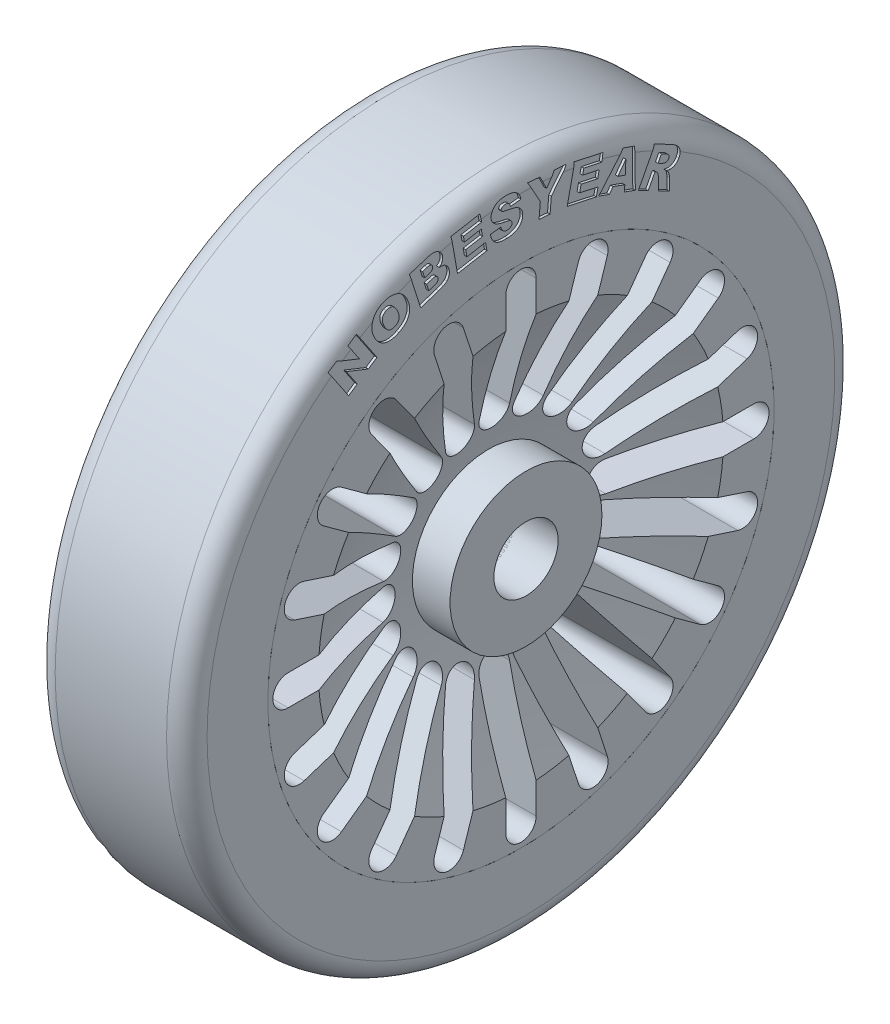
SolidWorks part; units mm, degrees
ref_plane "Front Plane" through (0, 0, 0) normal (0, 0, 1) x (1, 0, 0)
ref_plane "Top Plane" through (0, 0, 0) normal (0, 1, 0) x (1, 0, 0)
ref_plane "Right Plane" through (0, 0, 0) normal (1, 0, 0) x (0, 0, -1)
ref_axis "Axis1" through (-1.5, 0, 0) along (1, 0, 0)
sketch "Sketch1" plane through (0, 0, 0) normal (0, 0, 1) x (1, 0, 0)
  line L0 (-3.75, 0) -> (3.75, 0)
  line L1 (7.5, 20) -> (7.5, 25)
  line L2 (7.5, 25) -> (-7.5, 25)
  line L3 (-7.5, 25) -> (-7.5, 20)
  line L4 (0, -55) -> (0, 55) construction
  line L5 (-1.5, 0) -> (31.5, 0) construction
  arc A0 (3.75, 0) -> (7.5, 20) centre (58.9583, 0) cw
  arc A1 (-7.5, 20) -> (-3.75, 0) centre (-58.9583, 0) cw
  point P2 (0, 0)
  point P10 (0, 25)
  dimension "D1" = 7.5
  dimension "D2" = 15
  dimension "D3" = 25
  dimension "D4" = 5
  dimension "D5" = 5
revolve "Hub" add sketch "Sketch1" angle 360 about L0
sketch "Sketch2" plane through (0, 0, 0) normal (0, 0, 1) x (1, 0, 0)
  line L0 (-7.5, 25) -> (7.5, 25)
  line L1 (7.5, 25) -> (7.5, 33)
  line L2 (-7.5, 33) -> (7.5, 33)
  line L3 (0, -27.5) -> (0, 27.5) construction
  line L5 (-1.5, 0) -> (31.5, 0) construction
  line L15 (-7.5, 33) -> (-7.5, 25)
  point P4 (0, 25)
  dimension "D1" = 8
  dimension "D2" = 25
  dimension "D3" = 15
revolve "Tire" add sketch "Sketch2" angle 360 about axis through (-1.5, 0, 0) along (1, 0, 0)
fillet "Fillet1" radius 2 2 edges at (-7.5, 0, 33) (7.5, 0, 33)
sketch "Sketch3" plane through (0, 0, 0) normal (1, 0, 0) x (0, 0, -1)
  circle A0 centre (0, 0) radius 7.5
  dimension "D1" = 15
extrude "Boss-Extrude1" add sketch "Sketch3" along normal mid plane 16 separate body
sketch "Sketch4" plane through (8, 0, 0) normal (1, 0, 0) x (0, 0, -1)
  circle A0 centre (0, 0) radius 3.175
  dimension "D1" = 6.35
extrude "AXEL HOLE" cut sketch "Sketch4" against normal through all
sketch "Sketch5" plane through (0, 0, 0) normal (1, 0, 0) x (0, 0, -1)
  line L0 (0, 11) -> (0, 23) construction
  line L1 (-1.5, 11) -> (-1.5, 23)
  line L2 (1.5, 11) -> (1.5, 23)
  arc A0 (-1.5, 11) -> (1.5, 11) centre (0, 11) ccw
  arc A1 (1.5, 23) -> (-1.5, 23) centre (0, 23) ccw
  point P3 (0, 17)
  dimension "D1" = 11
  dimension "D2" = 12
  dimension "D3" = 3
extrude "SPOKE Hole" cut sketch "Sketch5" against normal through all both and the other way through all
pattern_circular "CirPattern1" count 20 over 360 about axis through (0, 0, 0) along (1, 0, 0) of "SPOKE Hole"
sketch "Sketch6" plane through (7.5, 0, 0) normal (1, 0, 0) x (0, 0, -1)
  arc A0 (-20.919, 18.6117) -> (18.6117, 20.919) centre (0, 0) cw construction
  text T0 "NOBESYEAR" font "Arial Black" height 3.5
  dimension "D1" = 28
extrude "NAME PLATE" cut sketch "Sketch6" against normal blind 0.25
